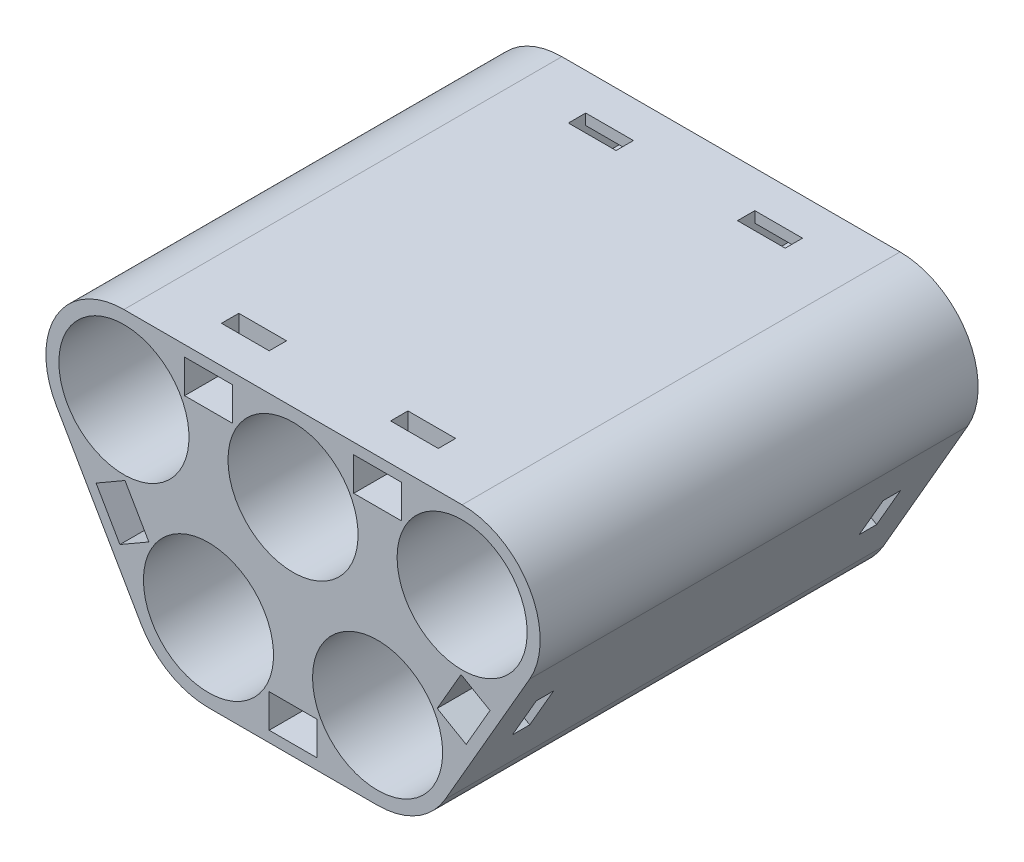
SolidWorks part; units mm, degrees
ref_plane "Front Plane" through (0, 0, 0) normal (0, 0, 1) x (1, 0, 0)
ref_plane "Top Plane" through (0, 0, 0) normal (0, 1, 0) x (1, 0, 0)
ref_plane "Right Plane" through (0, 0, 0) normal (1, 0, 0) x (0, 0, -1)
sketch "Sketch1" plane through (0, 0, 0) normal (0, 0, 1) x (1, 0, 0)
  line L0 (0, 9) -> (39, 9) construction
  line L1 (1.9558, -21.3875) -> (-7.7942, -4.5) construction
  line L2 (29.25, -25.8875) -> (9.75, -25.8875) construction
  line L3 (46.7942, -4.5) -> (37.0442, -21.3875) construction
  line L4 (0, 9) -> (39, 9)
  line L5 (1.9558, -21.3875) -> (-7.7942, -4.5)
  line L6 (29.25, -25.8875) -> (9.75, -25.8875)
  line L7 (46.7942, -4.5) -> (37.0442, -21.3875)
  arc A0 (46.7942, -4.5) -> (39, 9) centre (39, 0) ccw construction
  arc A1 (0, 9) -> (-7.7942, -4.5) centre (0, 0) ccw construction
  arc A2 (1.9558, -21.3875) -> (9.75, -25.8875) centre (9.75, -16.8875) ccw construction
  arc A3 (29.25, -25.8875) -> (37.0442, -21.3875) centre (29.25, -16.8875) ccw construction
  arc A4 (46.7942, -4.5) -> (39, 9) centre (39, 0) ccw
  arc A5 (0, 9) -> (-7.7942, -4.5) centre (0, 0) ccw
  arc A6 (1.9558, -21.3875) -> (9.75, -25.8875) centre (9.75, -16.8875) ccw
  arc A7 (29.25, -25.8875) -> (37.0442, -21.3875) centre (29.25, -16.8875) ccw
  circle A8 centre (0, 0) radius 7.5 construction
  circle A9 centre (9.75, -16.8875) radius 7.5 construction
  circle A10 centre (19.5, 0) radius 7.5 construction
  circle A11 centre (39, 0) radius 7.5 construction
  circle A12 centre (29.25, -16.8875) radius 7.5 construction
  circle A13 centre (0, 0) radius 7.5
  circle A14 centre (9.75, -16.8875) radius 7.5
  circle A15 centre (19.5, 0) radius 7.5
  circle A16 centre (39, 0) radius 7.5
  circle A17 centre (29.25, -16.8875) radius 7.5
extrude "Boss-Extrude1" add sketch "Sketch1" along normal up to surface (50.5 mm away)
sketch "Sketch2" plane through (37.0442, -21.3875, 0) normal (0.866, -0.5, 0) x (0, 0, -1)
  line L0 (0, 0) -> (0, 19.5) construction
  line L1 (0, 0) -> (0, 19.5)
  line L2 (-4.25, 7) -> (-6.25, 7)
  line L3 (-4.5, 12.25) -> (-6, 12.25)
  line L4 (-4.5, 12.25) -> (-4.5, 7.25)
  line L5 (-4.5, 7.25) -> (-6, 7.25)
  line L6 (-6, 12.25) -> (-6, 7.25)
  line L7 (-6.25, 12.5) -> (-6.25, 7)
  line L8 (-4.25, 12.5) -> (-6.25, 12.5)
  line L9 (-4.25, 12.5) -> (-4.25, 7)
  dimension "D1" = 1.5
  dimension "D2" = 0.25
extrude "Cut-Extrude1" cut sketch "Sketch2" against normal blind 1.5 contours L9 L2 L7 L8
sketch "Sketch3" plane through (0, 9, 0) normal (0, 1, 0) x (1, 0, 0)
  line L0 (32, -4.25) -> (32, -6.25)
  line L1 (31.75, -4.5) -> (26.75, -4.5)
  line L2 (31.75, -4.5) -> (31.75, -6)
  line L3 (31.75, -6) -> (26.75, -6)
  line L4 (26.75, -4.5) -> (26.75, -6)
  line L5 (32, -6.25) -> (26.5, -6.25)
  line L6 (26.5, -4.25) -> (26.5, -6.25)
  line L7 (32, -4.25) -> (26.5, -4.25)
  dimension "D1" = 1.5
  dimension "D2" = 0.25
extrude "Cut-Extrude2" cut sketch "Sketch3" against normal blind 1.5 contours L7 L6 L5 L0
sketch "Sketch4" plane through (0, -25.8875, 0) normal (0, -1, 0) x (1, 0, 0)
  line L8 (22.25, 4.25) -> (22.25, 6.25)
  line L9 (22.25, 6.25) -> (16.75, 6.25)
  line L10 (16.75, 6.25) -> (16.75, 4.25)
  line L11 (16.75, 4.25) -> (22.25, 4.25)
  line L12 (22.25, 4.25) -> (22.25, 6.25)
  line L13 (22.25, 6.25) -> (16.75, 6.25)
  line L14 (16.75, 6.25) -> (16.75, 4.25)
  line L15 (16.75, 4.25) -> (22.25, 4.25)
  dimension "D1" = 0.25
extrude "Cut-Extrude3" cut sketch "Sketch4" against normal blind 1.5
sketch "Sketch5" plane through (0, 0, 0) normal (0, 0, -1) x (-1, 0, 0)
  line L0 (-41.8702, -10.0287) -> (-39.3702, -14.3588)
  line L1 (-41.8702, -10.0287) -> (-38.9655, -8.3516)
  line L2 (-39.3702, -14.3588) -> (-36.4655, -12.6818)
  line L3 (-38.9655, -8.3516) -> (-36.4655, -12.6818)
  line L4 (-42.2117, -9.9372) -> (-39.4617, -14.7003)
  line L5 (-39.4617, -14.7003) -> (-36.1239, -12.7733)
  line L6 (-38.8739, -8.0101) -> (-36.1239, -12.7733)
  line L7 (-42.2117, -9.9372) -> (-38.8739, -8.0101)
  line L8 (-31.75, 7.5) -> (-26.75, 7.5) construction
  line L9 (-22, -24.3875) -> (-17, -24.3875) construction
  line L10 (-32, 7.75) -> (-26.5, 7.75)
  line L11 (-32, 7.75) -> (-32, 3.8959)
  line L12 (-32, 3.8959) -> (-26.5, 3.8959)
  line L13 (-26.5, 7.75) -> (-26.5, 3.8959)
  line L14 (-32, 7.75) -> (-26.5, 3.8959) construction
  line L15 (-32, 3.8959) -> (-26.5, 7.75) construction
  line L17 (-22.25, -20.7834) -> (-16.75, -20.7834)
  line L18 (-22.25, -20.7834) -> (-22.25, -24.6375)
  line L19 (-22.25, -24.6375) -> (-16.75, -24.6375)
  line L20 (-16.75, -20.7834) -> (-16.75, -24.6375)
  line L21 (-22.25, -20.7834) -> (-16.75, -24.6375) construction
  line L22 (-22.25, -24.6375) -> (-16.75, -20.7834) construction
  point P14 (-29.25, 5.8229)
  point P20 (-29.25, 7.5)
  point P24 (-19.5, -22.7104)
  point P30 (-19.5, -24.3875)
  dimension "D1" = 3.3541
  dimension "D3" = 0.25
  dimension "D4" = 0.25
  dimension "D2" = 0.25
extrude "Cut-Extrude4" cut sketch "Sketch5" against normal blind 6.25 contours L13 L10 L11 L12 | L20 L17 L18 L19 | L6 L5 L4 L7
ref_plane "Plane1" through (19.5, 0, 0) normal (-1, 0, 0) x (0, 0, 1)
mirror "Mirror2" about plane through (19.5, 0, 0) normal (-1, 0, 0) of "Cut-Extrude4", "Cut-Extrude3", "Cut-Extrude2", "Cut-Extrude1"
ref_plane "Plane2" through (0, 0, 25.25) normal (0, 0, -1) x (-1, 0, 0)
mirror "Mirror3" about plane through (0, 0, 25.25) normal (0, 0, -1) of "Mirror2", "Cut-Extrude4", "Cut-Extrude3", "Cut-Extrude2", "Cut-Extrude1"
equation "\"D1@Sketch5\"=sqr( 5)*1.5"
equation "\"D1@Cut-Extrude4\"=6.00mm+.25"
